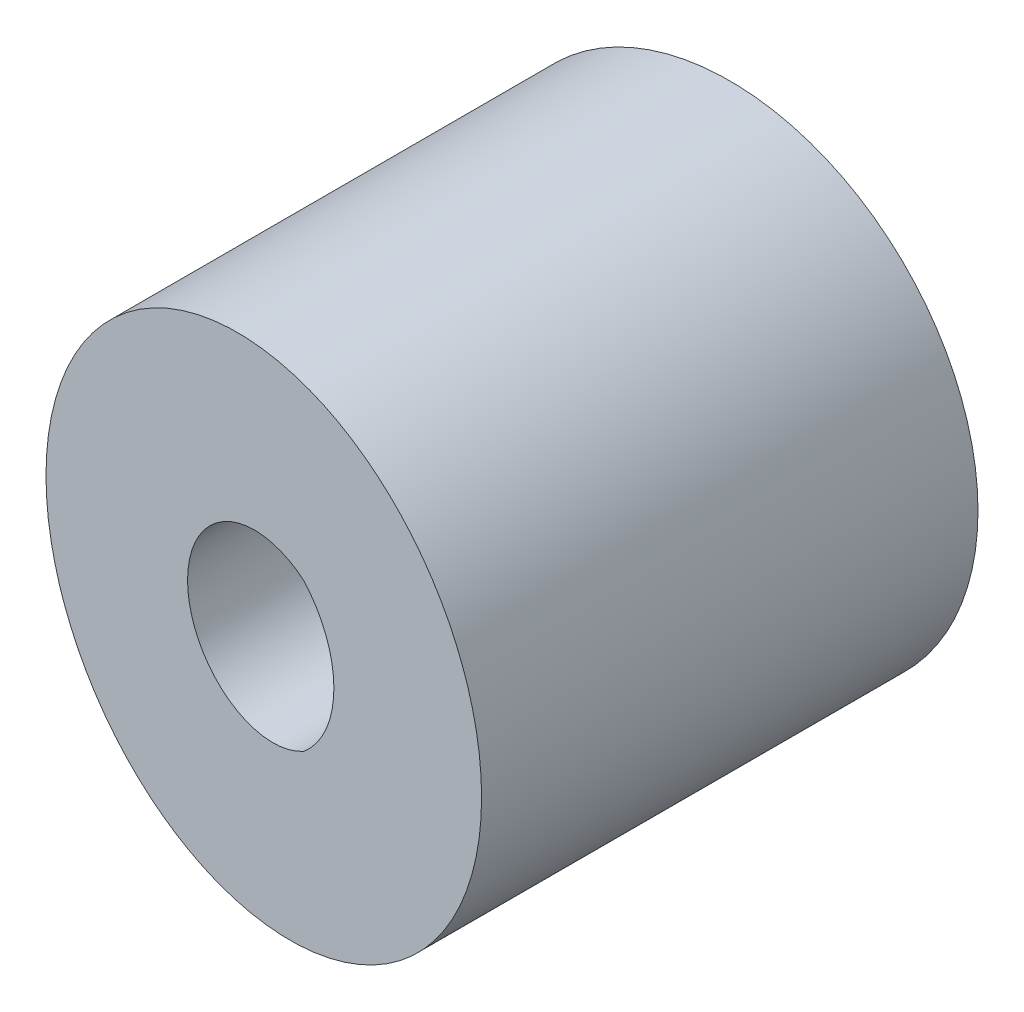
SolidWorks part; units mm, degrees
ref_plane "Front Plane" through (0, 0, 0) normal (0, 0, 1) x (1, 0, 0)
ref_plane "Top Plane" through (0, 0, 0) normal (0, 1, 0) x (1, 0, 0)
ref_plane "Right Plane" through (0, 0, 0) normal (1, 0, 0) x (0, 0, -1)
sketch "Sketch1" plane through (0, 0, 0) normal (0, 0, 1) x (1, 0, 0)
  circle A0 centre (0, 0) radius 10
  dimension "D1" = 20
extrude "Boss-Extrude1" add sketch "Sketch1" along normal blind 20
sketch "Sketch2" plane through (0, 0, 0) normal (0, 1, 0) x (1, 0, 0)
  line L0 (-175.1904, 2.6858) -> (24.8096, -21.8142)
  line L1 (24.8096, -21.8142) -> (24.8096, -148.8142)
  line L2 (24.8096, -148.8142) -> (-175.1904, -173.3142)
  line L3 (-175.1904, -173.3142) -> (-175.1904, 2.6858)
  line L4 (-175.1904, -85.3142) -> (24.8096, -85.3142) construction
  line L5 (0, 0) -> (0, -18.775) construction
  dimension "D1" = 127
  dimension "D2" = 176
  dimension "D3" = 200
  dimension "D4" = 176.5
extrude "Cut-Extrude1" cut sketch "Sketch2" against normal mid plane 206
hole_wizard "M8x1.0 Tapped Hole1" positions "Sketch4" profile "Sketch3" tap size "M8x1.0" standard "ISO"
sketch "Sketch4" plane through (0, 0, 0) normal (0, 0, -1) x (-1, 0, 0)
  point P0 (0, 0)
sketch "Sketch3" plane through (0, 0, 0) normal (1, 0, 0) x (0, 1, 0)
  line L0 (0, 0) -> (0, 21.103)
  line L1 (0, 21.103) -> (3.5, 19)
  line L2 (3.5, 19) -> (3.5, 0)
  line L5 (3.5, 0) -> (0, 0)
  line L10 (0, 21.103) -> (-3.5, 19) construction
  line L11 (0, -6.35) -> (0, 107.95) construction
  dimension "Tap Drill Dia." = 7
  dimension "Tap Drill Depth" = 19
  dimension "Drill Angle" = 118
cosmetic thread "Hole Thread1" parameters "D1"=16, "D2"=8
